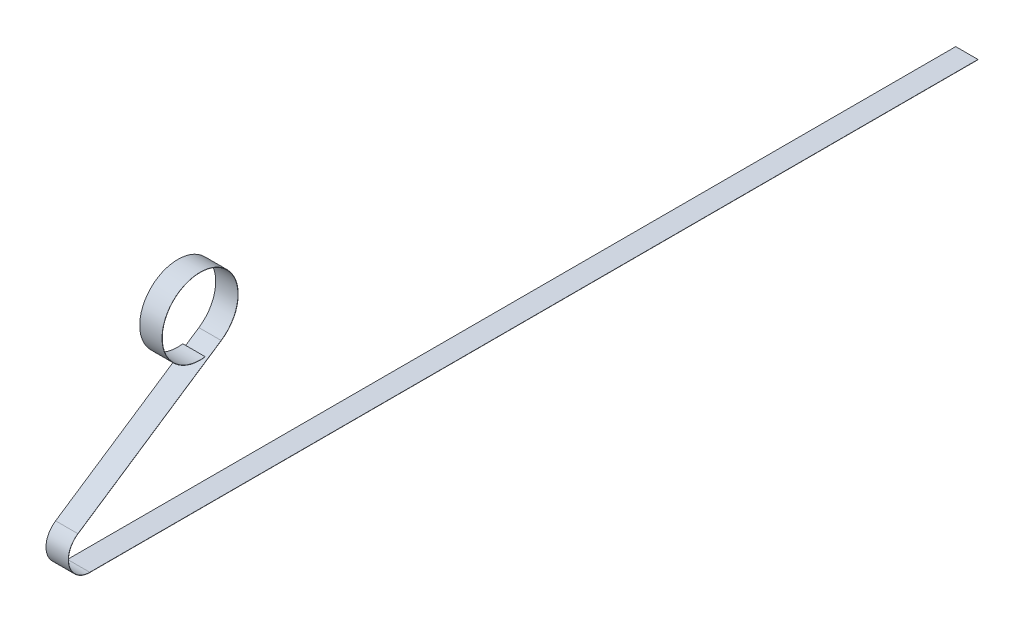
SolidWorks part; units mm, degrees
ref_plane "Front Plane" through (0, 0, 0) normal (0, 0, 1) x (1, 0, 0)
ref_plane "Top Plane" through (0, 0, 0) normal (0, 1, 0) x (1, 0, 0)
ref_plane "Right Plane" through (0, 0, 0) normal (1, 0, 0) x (0, 0, -1)
sketch "Sketch1" plane through (0, 0, 0) normal (0, 0, 1) x (1, 0, 0)
  line L1 (0, 0) -> (25.4, 0)
  line L2 (0, 0) -> (0, 0.254)
  line L3 (0, 0.254) -> (25.4, 0.254)
  line L4 (25.4, 0) -> (25.4, 0.254)
  dimension "D1" = 0.254
  dimension "D2" = 25.4
extrude "Boss-Extrude1" add sketch "Sketch1" along normal blind 1012.444 contours L3 L4 L1 L2
sketch "Sketch3" plane through (0, 0, 1012.444) normal (0, 0, 1) x (1, 0, 0)
  line L1 (0, 0) -> (25.4, 0)
  line L2 (0, 0) -> (0, 0.254)
  line L3 (0, 0.254) -> (25.4, 0.254)
  line L4 (25.4, 0) -> (25.4, 0.254)
sketch "Sketch5" plane through (0, 0, 0) normal (1, 0, 0) x (0, 0, -1)
  line L0 (-1025.8577, 44.9139) -> (-862.5492, 154.0031)
  arc A1 (-880.8975, 147.0722) -> (-862.5492, 154.0031) centre (-886.6752, 190.1202) cw
  arc A2 (-1025.8577, 44.9139) -> (-1012.444, 0.254) centre (-1012.3133, 24.6376) ccw
sweep "Sweep12" add profiles "Sketch3" path "Sketch5"
